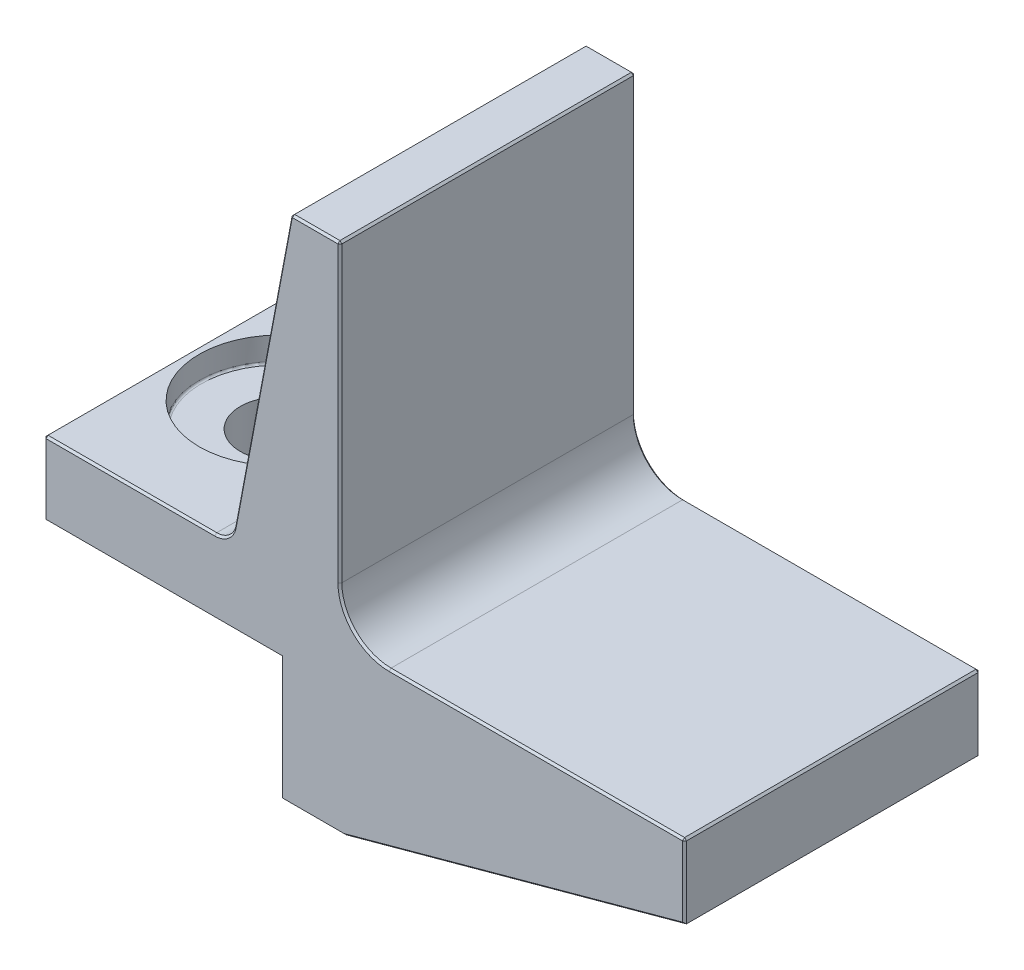
SolidWorks part; units mm, degrees
material "7075-T6 (SN)"
ref_plane "Front Plane" through (0, 0, 0) normal (0, 0, 1) x (1, 0, 0)
ref_plane "Top Plane" through (0, 0, 0) normal (0, 1, 0) x (1, 0, 0)
ref_plane "Right Plane" through (0, 0, 0) normal (1, 0, 0) x (0, 0, -1)
sketch "Sketch1" plane through (0, 0, 0) normal (0, 0, 1) x (1, 0, 0)
  line L0 (0, 0) -> (44.45, 0)
  line L1 (44.45, 0) -> (44.45, -9.525)
  line L2 (-7.6808, -5.6421) -> (-38.1608, -5.6421)
  line L3 (-38.1608, -5.6421) -> (-38.1608, 3.8829)
  line L4 (-38.1608, 3.8829) -> (-14.0308, 3.8829)
  line L5 (-14.0308, 3.8829) -> (-6.35, 44.45)
  line L6 (-6.35, 44.45) -> (0, 44.45)
  line L7 (0, 44.45) -> (0, 0)
  line L8 (-7.6808, -5.6421) -> (-7.6808, -21.5171)
  line L9 (-7.6808, -21.5171) -> (0.5742, -21.5171)
  line L10 (0.5742, -21.5171) -> (44.45, -9.525)
  dimension "D1" = 44.45
  dimension "D2" = 44.45
  dimension "D3" = 9.525
  dimension "D4" = 38.1608
  dimension "D5" = 6.35
  dimension "D6" = 24.13
  dimension "D7" = 30.48
  dimension "D8" = 9.525
  dimension "D9" = 15.875
  dimension "D10" = 8.255
  dimension "D11" = 3.8829
extrude "Boss-Extrude1" add sketch "Sketch1" along normal blind 38.1
hole_wizard "CBORE for 3/8 Binding Head Machine Screw1" positions "Sketch6" profile "Sketch3" counterbore size "3/8" standard "ANSI Inch" end condition through all
sketch "Sketch6" plane through (0, 3.8829, 0) normal (0, 1, 0) x (1, 0, 0)
  line L1 (-38.1608, -38.1) -> (-38.1608, 0) construction
  point P0 (-26.8578, -19.05)
  point P8 (-38.1608, -19.05)
  dimension "D1" = 11.303
sketch "Sketch3" plane through (-26.8578, 3.8829, 19.05) normal (1, 0, 0) x (0, 0, 1)
  line L0 (0, 0) -> (0, 25.4)
  line L1 (0, 25.4) -> (5.0419, 25.4)
  line L3 (5.0419, 25.4) -> (5.0419, 3.175)
  line L4 (10.3378, 3.175) -> (5.0419, 3.175)
  line L5 (10.3378, 3.175) -> (10.3378, 0)
  line L7 (10.3378, 0) -> (0, 0)
  line L11 (0, 0) -> (0, 107.95) construction
  dimension "Thru Hole Dia." = 10.0838
  dimension "Thru Hole Depth" = 25.4
  dimension "C'Bore Depth" = 3.175
fillet "Fillet1" radius 2.54 1 edges at (-14.0308, 3.8829, 19.05)
fillet "Fillet2" radius 6.35 1 edges at (0, 0, 19.05)
chamfer "Chamfer1" distance 0.254 angle 45 31 edges at (-6.35, 44.45, 19.05) (-3.175, 44.45, 0) (-9.9947, 25.2002, 0) (-14.5146, 4.4669, 0) (-27.1479, 3.8829, 0) (-38.1608, -0.8796, 0) (-22.9208, -5.6421, 0) (44.45, -4.7625, 0) (25.4, 0, 0) (1.8599, 1.8599, 0) (0, 25.4, 0) (44.45, -4.7625, 38.1) (-22.9208, -5.6421, 38.1) (-38.1608, -5.6421, 19.05) (-38.1608, -0.8796, 38.1) (-38.1608, 3.8829, 19.05) (-27.1479, 3.8829, 38.1) (-14.5146, 4.4669, 38.1) (-9.9947, 25.2002, 38.1) (-3.175, 44.45, 38.1) (0, 44.45, 19.05) (0, 25.4, 38.1) (1.8599, 1.8599, 38.1) (25.4, 0, 38.1) (44.45, 0, 19.05) (-7.6808, -13.5796, 0) (-3.5533, -21.5171, 0) (22.5121, -15.5211, 0) (22.5121, -15.5211, 38.1) (-3.5533, -21.5171, 38.1) (-7.6808, -13.5796, 38.1)
fillet "Fillet3" radius 0.254 1 edges at (-26.8578, 0.7079, 29.3878)
chamfer "Chamfer2" distance 0.254 angle 45 1 edges at (-31.8997, -5.6421, 19.05)
